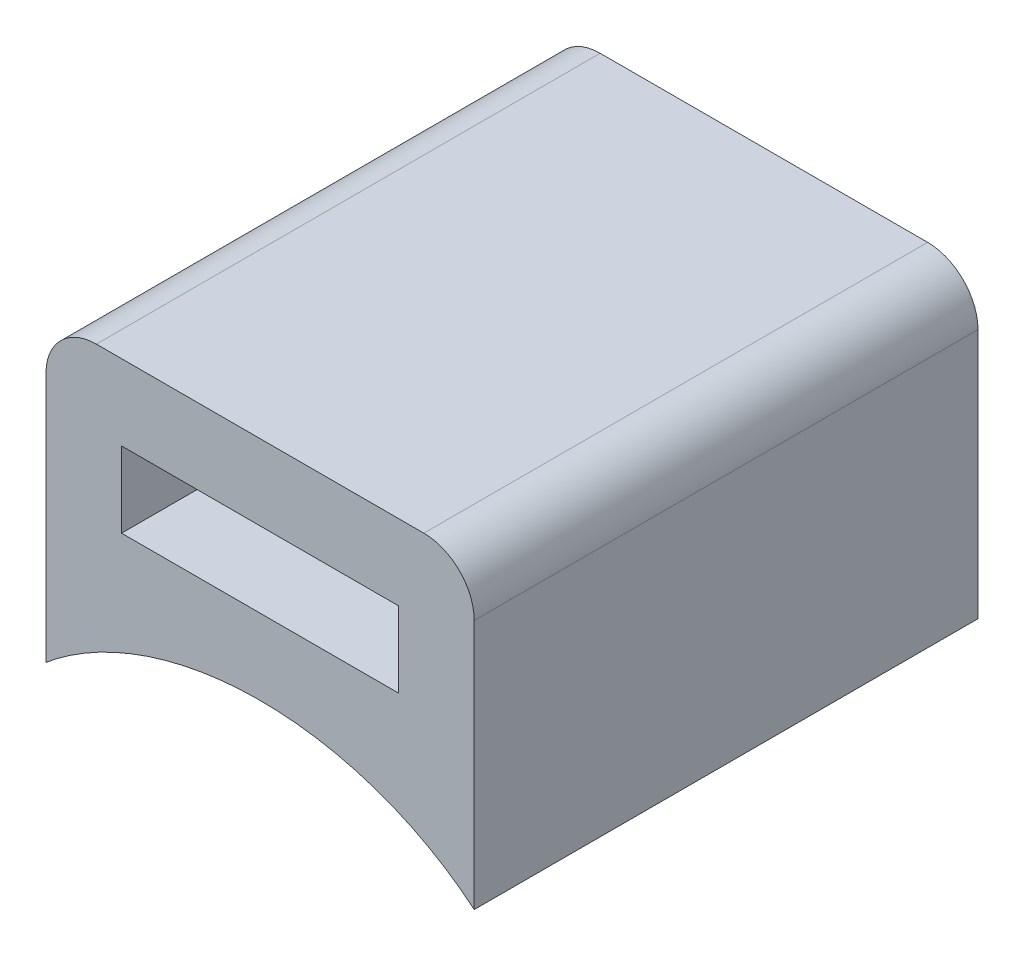
SolidWorks part; units mm, degrees
ref_plane "Front Plane" through (0, 0, 0) normal (0, 0, 1) x (1, 0, 0)
ref_plane "Top Plane" through (0, 0, 0) normal (0, 1, 0) x (1, 0, 0)
ref_plane "Right Plane" through (0, 0, 0) normal (1, 0, 0) x (0, 0, -1)
sketch "Sketch1" plane through (0, 0, 0) normal (0, 0, 1) x (1, 0, 0)
  line L0 (0, 12.065) -> (0, 10.16) construction
  line L1 (0, 8.255) -> (0, 6.35) construction
  line L2 (-3.4925, 9.2075) -> (-5.3975, 9.2075) construction
  line L3 (5.3975, 4.4823) -> (5.3975, 12.065)
  line L4 (5.3975, 12.065) -> (-5.3975, 12.065)
  line L5 (-5.3975, 12.065) -> (-5.3975, 4.4823)
  line L8 (-3.4925, 10.16) -> (3.4925, 10.16)
  line L9 (-3.4925, 10.16) -> (-3.4925, 8.255)
  line L10 (-3.4925, 8.255) -> (3.4925, 8.255)
  line L11 (3.4925, 10.16) -> (3.4925, 8.255)
  ellipse E0 centre (0, 0) end of major axis (-7.62, 0) minor radius 6.35
  point P14 (0, 12.065)
  point P17 (0, 10.16)
  dimension "D2" = 6.985
  dimension "D3" = 1.905
  dimension "D4" = 12.7
  dimension "D5" = 15.24
extrude "Boss-Extrude1" add sketch "Sketch1" along normal blind 12.7 contours E0 L3 L4 L5 L8 L11 L10 L9
fillet "Fillet1" radius 1.27 2 edges at (5.3975, 12.065, 6.35) (-5.3975, 12.065, 6.35)
